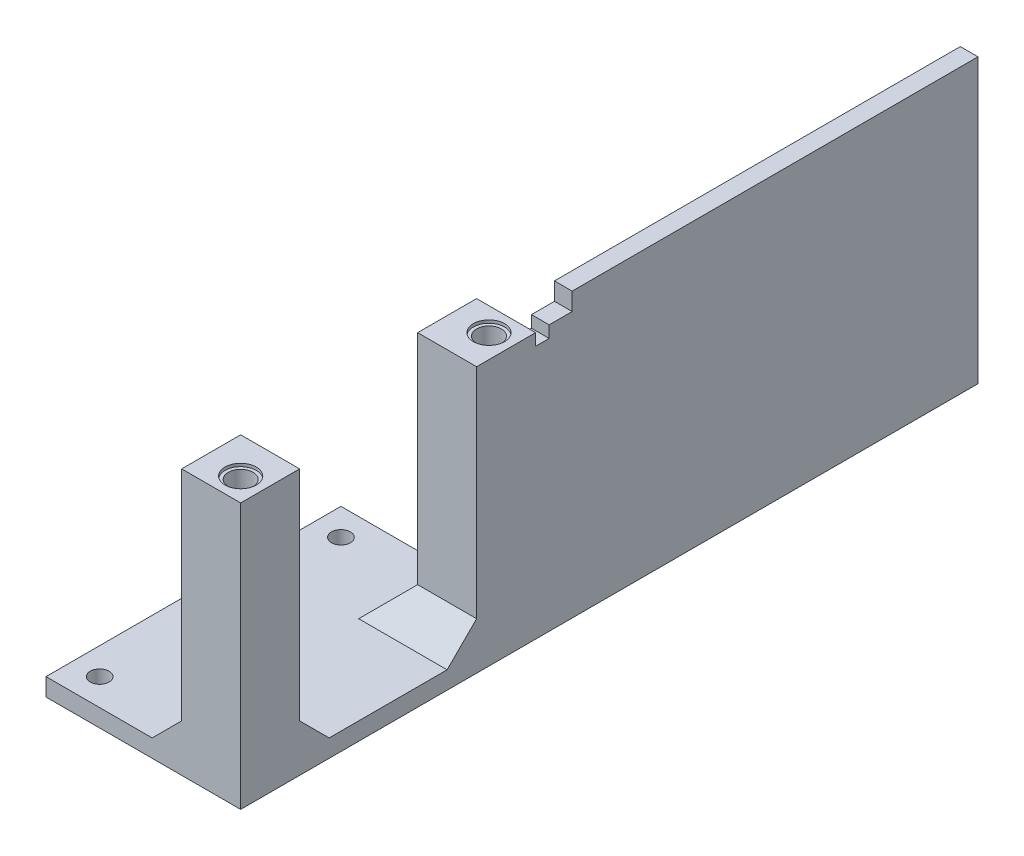
SolidWorks part; units mm, degrees
ref_plane "Front Plane" through (0, 0, 0) normal (0, 0, 1) x (1, 0, 0)
ref_plane "Top Plane" through (0, 0, 0) normal (0, 1, 0) x (1, 0, 0)
ref_plane "Right Plane" through (0, 0, 0) normal (1, 0, 0) x (0, 0, -1)
sketch "Sketch1" plane through (0, 0, 0) normal (0, 1, 0) x (1, 0, 0)
  line L1 (-6.5124, 9.686) -> (1.4876, 9.686)
  line L2 (-6.5124, 9.686) -> (-6.5124, -40.314)
  line L3 (-6.5124, -40.314) -> (1.4876, -40.314)
  line L4 (1.4876, 9.686) -> (1.4876, -40.314)
  line L5 (1.4876, 9.686) -> (26.4876, 9.686)
  line L6 (1.4876, 9.686) -> (1.4876, -40.314)
  line L7 (1.4876, -40.314) -> (26.4876, -40.314)
  line L8 (26.4876, 9.686) -> (26.4876, -40.314)
  circle A0 centre (-1.9624, -35.764) radius 1.6
  circle A1 centre (-1.9624, 5.136) radius 1.6
  dimension "D4" = 3.2
  dimension "D5" = 3.2
  dimension "D6" = 4.55
  dimension "D7" = 4.55
  dimension "D8" = 4.55
  dimension "D9" = 4.55
  dimension "D1" = 8
  dimension "D2" = 50
  dimension "D3" = 25
extrude "Boss-Extrude1" add sketch "Sketch1" along normal blind 3 contours A1 | A0 | L5 L8 L7 L3 L2 L1
sketch "Sketch2" plane through (0, 3, 0) normal (0, 1, 0) x (1, 0, 0)
  line L1 (26.4876, -40.314) -> (16.4876, -40.314)
  line L2 (26.4876, -40.314) -> (26.4876, -30.314)
  line L3 (26.4876, -30.314) -> (16.4876, -30.314)
  line L4 (16.4876, -40.314) -> (16.4876, -30.314)
  line L5 (26.4876, 9.686) -> (16.4876, 9.686)
  line L6 (26.4876, 9.686) -> (26.4876, -0.314)
  line L7 (26.4876, -0.314) -> (16.4876, -0.314)
  line L8 (16.4876, 9.686) -> (16.4876, -0.314)
  dimension "D1" = 10
  dimension "D2" = 10
  dimension "D3" = 10
  dimension "D4" = 10
extrude "Boss-Extrude2" add sketch "Sketch2" along normal blind 42
chamfer "Chamfer1" distance 5 angle 45 4 edges at (16.4876, 3, -4.686) (21.4876, 3, 0.314) (16.4876, 3, 35.314) (21.4876, 3, 30.314)
ref_plane "Plane1" through (0, 45, 0) normal (0, 1, 0) x (1, 0, 0)
sketch "Sketch3" plane through (0, 45, 0) normal (0, 1, 0) x (1, 0, 0)
  line L0 (26.4876, -40.314) -> (26.4876, -30.314) construction
  line L1 (16.4876, -40.314) -> (26.4876, -40.314) construction
  line L2 (26.4876, -0.314) -> (26.4876, 9.686) construction
  line L3 (26.4876, 9.686) -> (16.4876, 9.686) construction
  circle A0 centre (22.5376, -36.364) radius 2.1
  circle A1 centre (22.5376, 5.736) radius 2.1
  dimension "D1" = 4.2
  dimension "D3" = 3.95
  dimension "D4" = 4.2
  dimension "D6" = 3.95
  dimension "D2" = 3.95
  dimension "D5" = 3.95
extrude "Cut-Extrude1" cut sketch "Sketch3" against normal blind 52
sketch "Sketch4" plane through (0, 45, 0) normal (0, 1, 0) x (1, 0, 0)
  circle A0 centre (22.5376, -36.364) radius 2.65
  circle A1 centre (22.5376, 5.736) radius 2.65
  dimension "D1" = 5.3
  dimension "D2" = 5.3
extrude "Cut-Extrude2" cut sketch "Sketch4" against normal blind 0.5
ref_plane "Plane2" through (0, 22.5, 0) normal (0, -1, 0) x (-1, 0, 0)
mirror "Mirror1" about plane through (0, 22.5, 0) normal (0, -1, 0) of "Cut-Extrude2"
sketch "Sketch5" plane through (0, 0, -9.686) normal (0, 0, -1) x (-1, 0, 0)
  line L0 (-26.4876, 45) -> (-26.4876, 0) construction
  line L1 (-26.4876, 43) -> (-23.4876, 43)
  line L2 (-26.4876, 43) -> (-26.4876, 0)
  line L3 (-26.4876, 0) -> (-23.4876, 0)
  line L4 (-23.4876, 43) -> (-23.4876, 0)
  line L5 (6.5124, 0) -> (-26.4876, 0) construction
  line L6 (5.5, 45) -> (-5.5, 45) construction
  dimension "D1" = 3
  dimension "D2" = 2
extrude "Boss-Extrude3" add sketch "Sketch5" along normal blind 75
sketch "Sketch6" plane through (0, 43, 0) normal (0, 1, 0) x (1, 0, 0)
  line L0 (23.4876, 84.686) -> (23.4876, 9.686) construction
  line L1 (23.4876, 11.986) -> (26.4876, 11.986)
  line L2 (23.4876, 11.986) -> (23.4876, 84.686)
  line L3 (23.4876, 84.686) -> (26.4876, 84.686)
  line L4 (26.4876, 11.986) -> (26.4876, 84.686)
  line L5 (26.4876, 9.686) -> (16.4876, 9.686) construction
  dimension "D1" = 2.3
extrude "Boss-Extrude4" add sketch "Sketch6" along normal blind 2
sketch "Sketch7" plane through (0, 45, 0) normal (0, 1, 0) x (1, 0, 0)
  line L0 (26.4876, 11.986) -> (26.4876, 84.686) construction
  line L1 (23.4876, 84.686) -> (26.4876, 84.686)
  line L2 (23.4876, 84.686) -> (23.4876, 15.886)
  line L3 (23.4876, 15.886) -> (26.4876, 15.886)
  line L4 (26.4876, 84.686) -> (26.4876, 15.886)
  line L5 (23.4876, 11.986) -> (26.4876, 11.986) construction
  dimension "D1" = 3.9
extrude "Boss-Extrude5" add sketch "Sketch7" along normal blind 3
